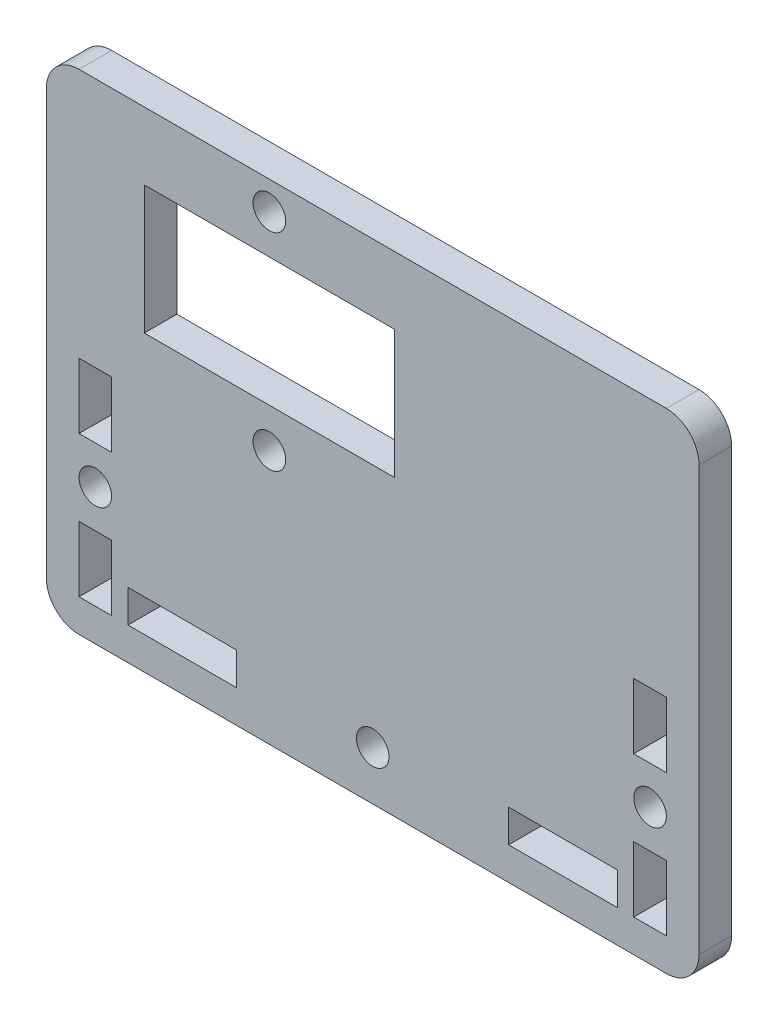
SolidWorks part; units mm, degrees
ref_plane "Plan de face" through (0, 0, 0) normal (0, 0, 1) x (1, 0, 0)
ref_plane "Plan de dessus" through (0, 0, 0) normal (0, 1, 0) x (1, 0, 0)
ref_plane "Plan de droite" through (0, 0, 0) normal (1, 0, 0) x (0, 0, -1)
sketch "Esquisse12" plane through (0, 0, 0) normal (0, 0, 1) x (1, 0, 0)
  line L0 (193.0803, 18.3353) -> (183.8219, 18.3353) construction
  line L1 (218.0803, -14.5647) -> (164.0803, -14.5647)
  line L2 (221.0803, -11.5647) -> (221.0803, 27.4353)
  line L3 (218.0803, 30.4353) -> (164.0803, 30.4353)
  line L4 (161.0803, -11.5647) -> (161.0803, 27.4353)
  line L5 (164.0803, -11.5647) -> (167.0803, -11.5647)
  line L6 (164.0803, -11.5647) -> (164.0803, -5.5647)
  line L7 (164.0803, -5.5647) -> (167.0803, -5.5647)
  line L8 (167.0803, -11.5647) -> (167.0803, -5.5647)
  line L9 (178.5803, -11.5647) -> (168.5803, -11.5647)
  line L10 (178.5803, -11.5647) -> (178.5803, -8.5647)
  line L11 (178.5803, -8.5647) -> (168.5803, -8.5647)
  line L12 (168.5803, -11.5647) -> (168.5803, -8.5647)
  line L13 (218.0803, -11.5647) -> (215.0803, -11.5647)
  line L14 (218.0803, -11.5647) -> (218.0803, -5.5647)
  line L15 (218.0803, -5.5647) -> (215.0803, -5.5647)
  line L16 (215.0803, -11.5647) -> (215.0803, -5.5647)
  line L17 (213.5803, -11.5647) -> (203.5803, -11.5647)
  line L18 (213.5803, -11.5647) -> (213.5803, -8.5647)
  line L19 (213.5803, -8.5647) -> (203.5803, -8.5647)
  line L20 (203.5803, -11.5647) -> (203.5803, -8.5647)
  line L21 (164.0803, 1.4353) -> (167.0803, 1.4353)
  line L22 (164.0803, 1.4353) -> (164.0803, 7.4353)
  line L23 (164.0803, 7.4353) -> (167.0803, 7.4353)
  line L24 (167.0803, 1.4353) -> (167.0803, 7.4353)
  line L25 (215.0803, 1.4353) -> (218.0803, 1.4353)
  line L26 (215.0803, 1.4353) -> (215.0803, 7.4353)
  line L27 (215.0803, 7.4353) -> (218.0803, 7.4353)
  line L28 (218.0803, 1.4353) -> (218.0803, 7.4353)
  line L29 (170.0803, 24.2353) -> (193.0803, 24.2353)
  line L30 (170.0803, 24.2353) -> (170.0803, 12.4353)
  line L31 (170.0803, 12.4353) -> (193.0803, 12.4353)
  line L32 (193.0803, 24.2353) -> (193.0803, 12.4353)
  arc A0 (164.0803, -14.5647) -> (161.0803, -11.5647) centre (164.0803, -11.5647) cw
  arc A1 (218.0803, -14.5647) -> (221.0803, -11.5647) centre (218.0803, -11.5647) ccw
  arc A2 (221.0803, 27.4353) -> (218.0803, 30.4353) centre (218.0803, 27.4353) ccw
  arc A3 (164.0803, 30.4353) -> (161.0803, 27.4353) centre (164.0803, 27.4353) ccw
  circle A4 centre (191.0803, -10.0647) radius 1.5
  circle A5 centre (181.5803, 8.8353) radius 1.5
  circle A6 centre (181.5803, 27.8353) radius 1.5
  circle A7 centre (216.5803, -2.0647) radius 1.5
  circle A8 centre (165.5803, -2.0647) radius 1.5
  point P8 (221.0803, -14.5647)
  point P11 (221.0803, 30.4353)
  point P14 (161.0803, 30.4353)
  dimension "D3" = 3
  dimension "D14" = 1.5
  dimension "D15" = 1.5
  dimension "D16" = 3
  dimension "D17" = 3
  dimension "D18" = 1.5
  dimension "D19" = 3
  dimension "D20" = 3.5
  dimension "D21" = 3.5
  dimension "D28" = 3
  dimension "D29" = 3
  dimension "D33" = 11.5
  dimension "D34" = 19
  dimension "D36" = 27
  dimension "D37" = 12.5
  dimension "D1" = 60
  dimension "D2" = 45
  dimension "D4" = 3
  dimension "D5" = 3
  dimension "D6" = 6
  dimension "D7" = 6
  dimension "D8" = 10
  dimension "D9" = 3
  dimension "D10" = 3
  dimension "D11" = 10
  dimension "D12" = 45
  dimension "D13" = 1.5
  dimension "D22" = 6
  dimension "D23" = 6
  dimension "D24" = 3
  dimension "D25" = 3
  dimension "D26" = 3.5
  dimension "D27" = 3.5
  dimension "D30" = 11.8
  dimension "D31" = 23
  dimension "D32" = 9
  dimension "D35" = 9.5
extrude "Boss.-Extru.12" add sketch "Esquisse12" along normal blind 3 separate body
